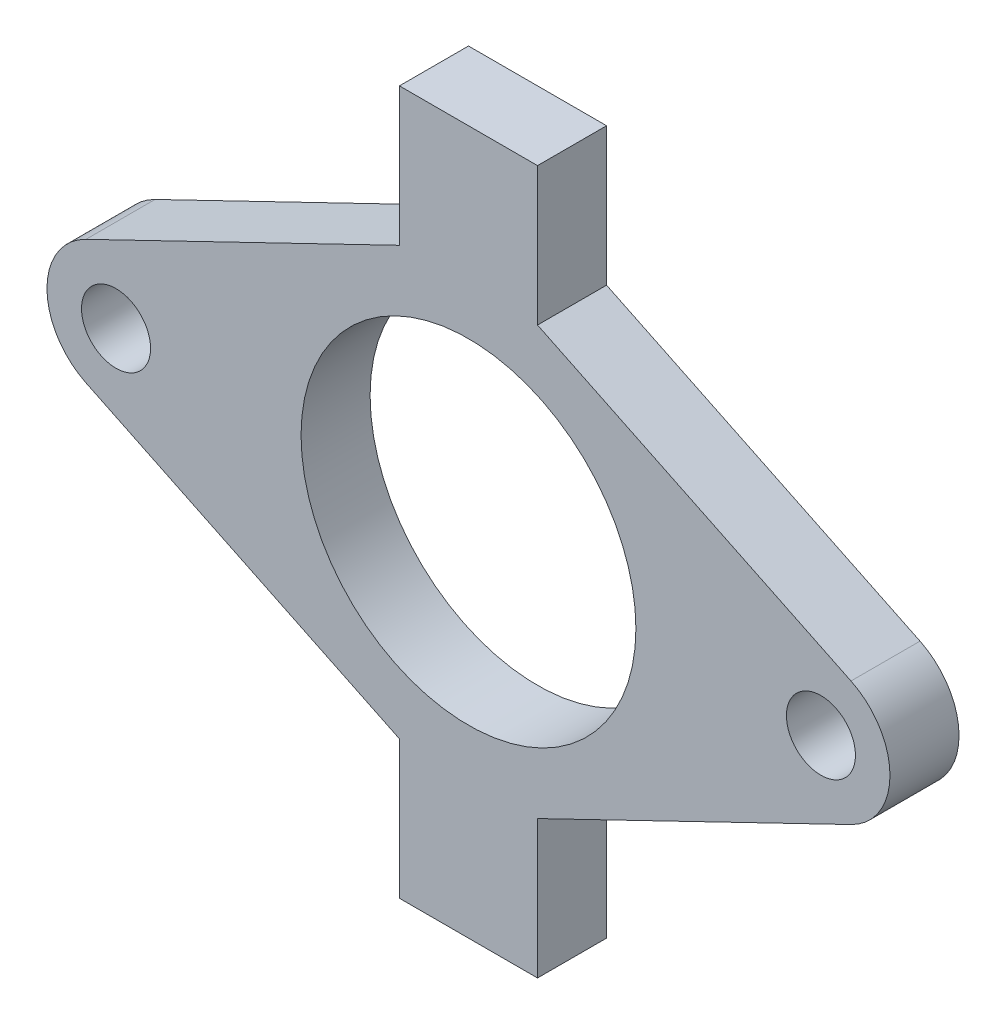
SolidWorks part; units mm, degrees
ref_plane "Front Plane" through (0, 0, 0) normal (0, 0, 1) x (1, 0, 0)
ref_plane "Top Plane" through (0, 0, 0) normal (0, 1, 0) x (1, 0, 0)
ref_plane "Right Plane" through (0, 0, 0) normal (1, 0, 0) x (0, 0, -1)
sketch "Sketch1" plane through (0, 0, 0) normal (0, 0, 1) x (1, 0, 0)
  line L1 (10, 54.25) -> (-10, 54.25)
  line L2 (-10, 54.25) -> (-10, 34.25)
  line L3 (-10, 34.25) -> (-55.4002, 12.3029)
  line L4 (-24.0245, 3.2997) -> (-74.0245, 3.2997) construction
  line L6 (10, -47.6506) -> (-10, -47.6506)
  line L7 (-10, -47.6506) -> (-10, -27.6506)
  line L8 (-10, -27.6506) -> (-55.4002, -5.7035)
  line L10 (0, 3.2997) -> (0, 38.9806) construction
  line L11 (10, -47.6506) -> (10, -27.6506)
  line L12 (10, -27.6506) -> (55.4002, -5.7035)
  line L13 (10, 34.25) -> (55.4002, 12.3029)
  line L14 (10, 54.25) -> (10, 34.25)
  arc A2 (-55.4002, 12.3029) -> (-55.4002, -5.7035) centre (-51.048, 3.2997) ccw
  circle A4 centre (0, 3.2997) radius 24.25
  arc A6 (55.4002, 12.3029) -> (55.4002, -5.7035) centre (51.048, 3.2997) cw
  circle A7 centre (51.048, 3.2997) radius 5
  circle A8 centre (-51.048, 3.2997) radius 5
  point P9 (0, -47.6506)
  point P16 (-61.048, 3.2997)
  point P25 (0, 54.25)
  dimension "D2" = 48.5
  dimension "D6" = 10
  dimension "D1" = 10
  dimension "D3" = 10
  dimension "D4" = 20
  dimension "D5" = 50
  dimension "D7" = 37.0235
extrude "Boss-Extrude1" add sketch "Sketch1" against normal blind 10
